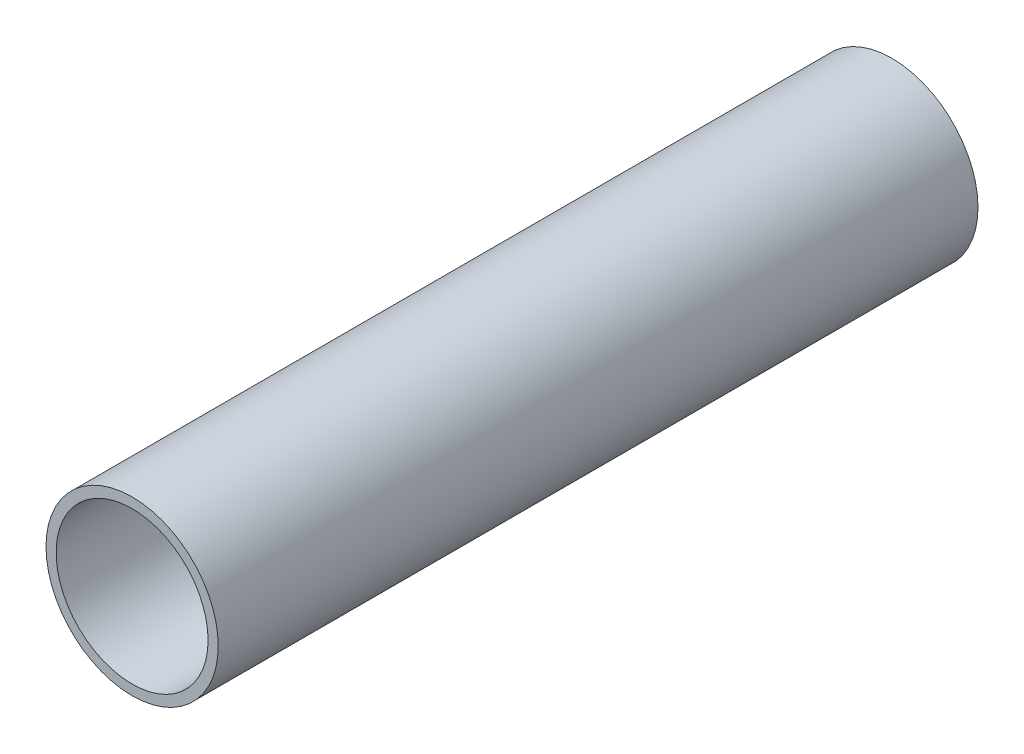
SolidWorks part; units mm, degrees
ref_plane "Front Plane" through (0, 0, 0) normal (0, 0, 1) x (1, 0, 0)
ref_plane "Top Plane" through (0, 0, 0) normal (0, 1, 0) x (1, 0, 0)
ref_plane "Right Plane" through (0, 0, 0) normal (1, 0, 0) x (0, 0, -1)
sketch "Sketch1" plane through (0, 0, 0) normal (0, 0, 1) x (1, 0, 0)
  circle A0 centre (0, 0) radius 30
  circle A1 centre (0, 0) radius 34
  dimension "D1" = 60
  dimension "D2" = 4
extrude "Boss-Extrude1" add sketch "Sketch1" along normal blind 300
